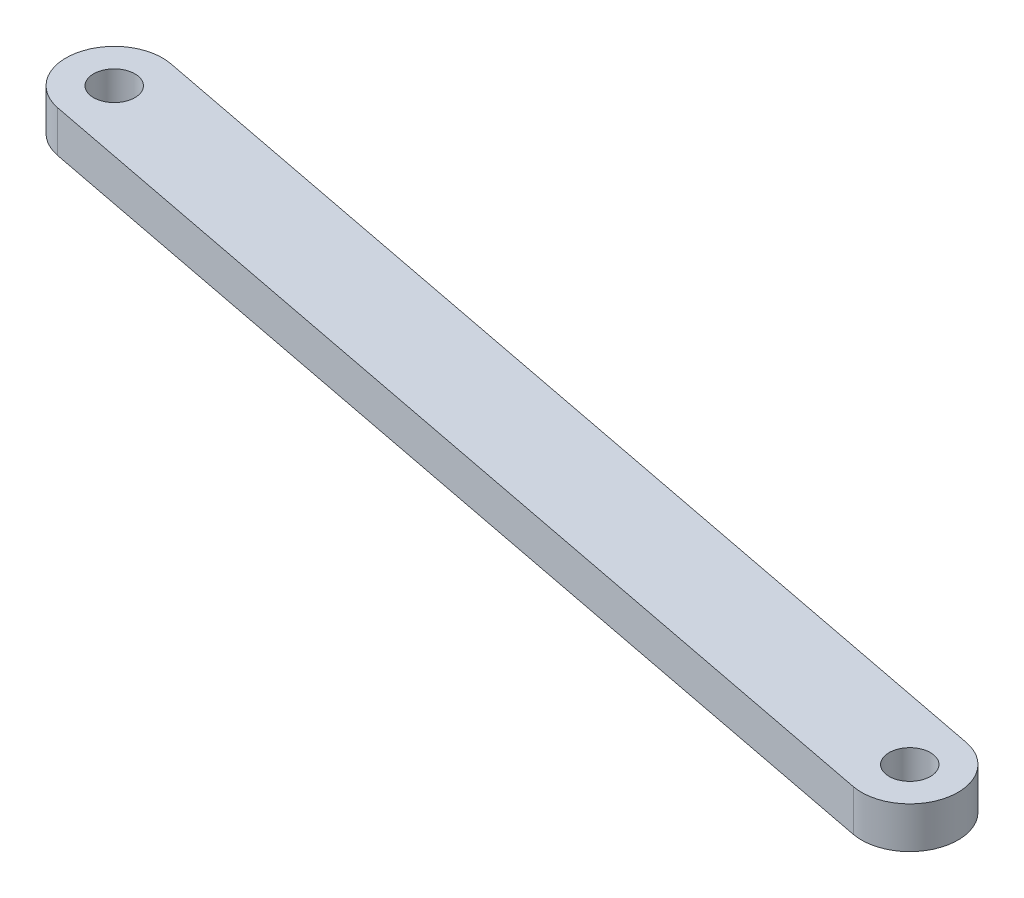
SolidWorks part; units mm, degrees
ref_plane "Front Plane" through (0, 0, 0) normal (0, 0, 1) x (1, 0, 0)
ref_plane "Top Plane" through (0, 0, 0) normal (0, 1, 0) x (1, 0, 0)
ref_plane "Right Plane" through (0, 0, 0) normal (1, 0, 0) x (0, 0, -1)
sketch "Sketch2" plane through (0, 84, 0) normal (0, 1, 0) x (1, 0, 0)
  line L0 (-5, 87.5) -> (-76.5046, 101.2894) construction
  line L1 (-75.8419, 104.7261) -> (-77.1674, 97.8527) construction
  line L2 (-4.3373, 90.9367) -> (-5.6628, 84.0633) construction
  line L3 (-5.6628, 84.0633) -> (-77.1674, 97.8527)
  line L4 (-75.8419, 104.7261) -> (-4.3373, 90.9367)
  circle A0 centre (-5, 87.5) radius 1.5 construction
  circle A1 centre (-76.5046, 101.2894) radius 1.0339 construction
  circle A2 centre (-5, 87.5) radius 1.5
  circle A3 centre (-76.5046, 101.2894) radius 1.0339 construction
  circle A4 centre (-76.5046, 101.2894) radius 1.5
  arc A5 (-77.1674, 97.8527) -> (-75.8419, 104.7261) centre (-76.5046, 101.2894) cw
  arc A6 (-4.3373, 90.9367) -> (-5.6628, 84.0633) centre (-5, 87.5) cw
  point P10 (-76.5046, 101.2894)
  point P13 (-5, 87.5)
  line M7 (39.7825, 110.0118) -> (-6.3498, 90.7293)
  arc M8 (-6.3498, 90.7293) -> (-3.6502, 84.2707) centre (-5, 87.5) ccw
  circle M11 centre (-5, 87.5) radius 1.5
  dimension "D1" = 2
extrude "Boss-Extrude2" add sketch "Sketch2" along normal blind 3 contours A6 L4 M7 M8 M11 | A5 L3 L4 A4 M8 M7
